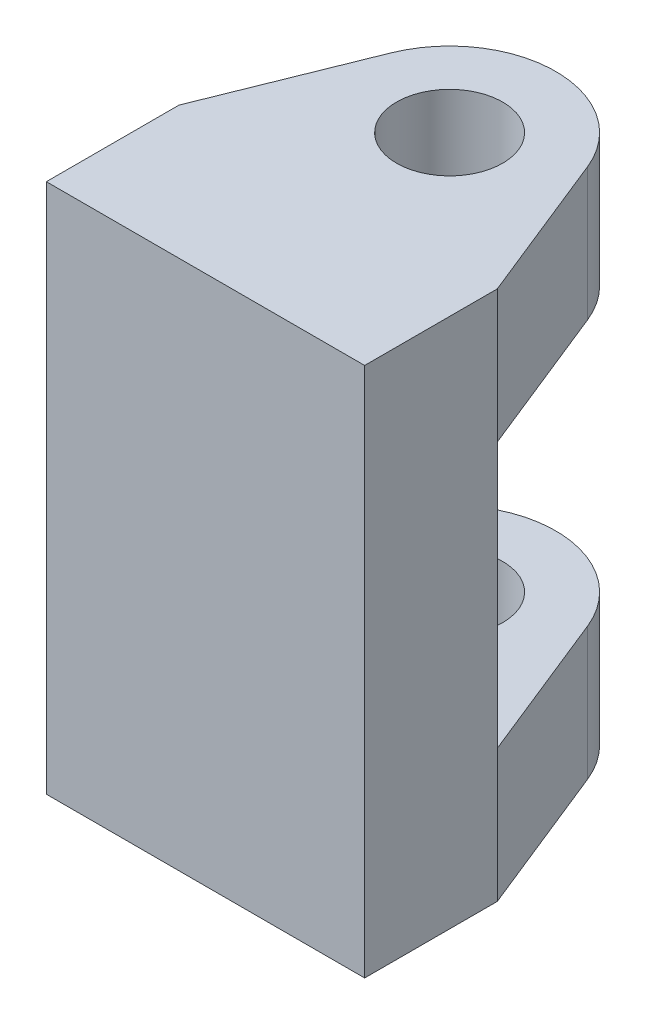
SolidWorks part; units mm, degrees
ref_plane "Front Plane" through (0, 0, 0) normal (0, 0, 1) x (1, 0, 0)
ref_plane "Top Plane" through (0, 0, 0) normal (0, 1, 0) x (1, 0, 0)
ref_plane "Right Plane" through (0, 0, 0) normal (1, 0, 0) x (0, 0, -1)
sketch "Sketch1" plane through (0, 0, 0) normal (0, 0, 1) x (1, 0, 0)
  line L1 (-6, -10) -> (6, -10)
  line L2 (-6, -10) -> (-6, 10)
  line L3 (-6, 10) -> (6, 10)
  line L4 (6, -10) -> (6, 10)
  line L5 (-6, -10) -> (6, 10) construction
  line L6 (-6, 10) -> (6, -10) construction
  point P0 (0, 0)
extrude "Boss-Extrude1" add sketch "Sketch1" along normal blind 5
sketch "Sketch2" plane through (0, 10, 0) normal (0, 1, 0) x (1, 0, 0)
  line L0 (-6, 0) -> (-3.7115, 5.6945)
  line L1 (6, 0) -> (3.7115, 5.6945)
  line L2 (-6, 0) -> (6, 0)
  circle A0 centre (0, 4.2029) radius 2
  arc A1 (3.7115, 5.6945) -> (-3.7115, 5.6945) centre (0, 4.2029) ccw
  dimension "D1" = 4
  dimension "D2" = 8
extrude "Boss-Extrude2" add sketch "Sketch2" against normal blind 5
mirror "Mirror1" about plane through (0, 0, 0) normal (0, 1, 0) of "Boss-Extrude2"
